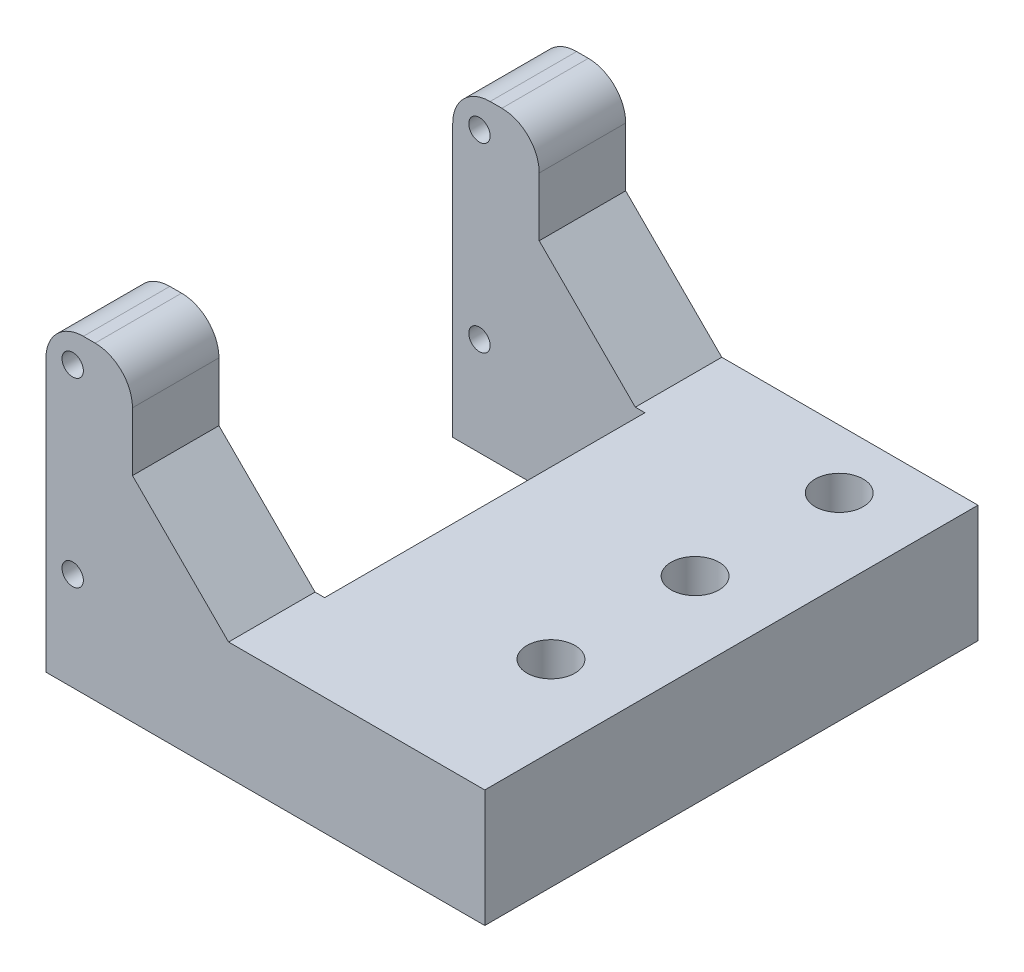
SolidWorks part; units mm, degrees
ref_plane "Plan de face" through (0, 0, 0) normal (0, 0, 1) x (1, 0, 0)
ref_plane "Plan de dessus" through (0, 0, 0) normal (0, 1, 0) x (1, 0, 0)
ref_plane "Plan de droite" through (0, 0, 0) normal (1, 0, 0) x (0, 0, -1)
sketch "Esquisse1" plane through (0, 0, 0) normal (0, 0, 1) x (1, 0, 0)
  line L1 (0, 0) -> (18, 0)
  line L2 (0, 0) -> (0, 29)
  line L3 (0, 29) -> (18, 29)
  line L4 (18, 0) -> (18, 29)
  dimension "D1" = 18
  dimension "D2" = 29
extrude "Boss.-Extru.1" add sketch "Esquisse1" along normal blind 46.2
sketch "Esquisse3" plane through (0, 0, 46.2) normal (0, 0, 1) x (1, 0, 0)
  line L0 (0, 29) -> (0, 0) construction
  line L3 (2.5, 9.2) -> (2.5, 26.2) construction
  line L4 (2.5, 26.2) -> (10.1767, 26.2) construction
  line L5 (0, 0) -> (18, 0) construction
  circle A2 centre (2.5, 26.2) radius 1
  circle A4 centre (2.5, 9.2) radius 1
  dimension "D1" = 2.5
  dimension "D5" = 17
  dimension "D3" = 2
  dimension "D2" = 9.2
extrude "Enlèv. mat.-Extru.1" cut sketch "Esquisse3" against normal through all
sketch "Esquisse4" plane through (0, 29, 0) normal (0, 1, 0) x (1, 0, 0)
  line L0 (0, -23.1) -> (18, -23.1) construction
  line L1 (0, -46.2) -> (0, 0) construction
  line L2 (18, -46.2) -> (18, 0) construction
  line L3 (0, -38.1) -> (0, -8.1)
  line L4 (0, -8.1) -> (18, -8.1)
  line L6 (18, -8.1) -> (18, -38.1)
  line L7 (18, 0) -> (0, 0) construction
  line L8 (0, -38.1) -> (18, -38.1)
  dimension "D1" = 8.1
extrude "Enlèv. mat.-Extru.2" cut sketch "Esquisse4" against normal through all
sketch "Esquisse5" plane through (0, 29, 0) normal (0, 1, 0) x (1, 0, 0)
  line L0 (18, 0) -> (0, 0) construction
  line L1 (18, -46.2) -> (26.1, -46.2)
  line L2 (18, -46.2) -> (18, 0)
  line L3 (18, 0) -> (26.1, 0)
  line L4 (26.1, -46.2) -> (26.1, 0)
  dimension "D1" = 8.1
extrude "Boss.-Extru.2" add sketch "Esquisse5" against normal up to vertex (29 mm away)
fillet "Congé1" radius 3.5 2 edges at (0, 29, 42.15) (0, 29, 4.05)
sketch "Esquisse7" plane through (0, 0, 0) normal (0, 0, -1) x (-1, 0, 0)
  line L1 (-26.1, 29) -> (-8.1, 29)
  line L2 (-26.1, 29) -> (-26.1, 11)
  line L3 (-26.1, 11) -> (-8.1, 11)
  line L4 (-8.1, 29) -> (-8.1, 11)
  dimension "D1" = 18
  dimension "D2" = 18
extrude "Enlèv. mat.-Extru.4" cut sketch "Esquisse7" against normal up to vertex
sketch "Esquisse8" plane through (0, 11, 0) normal (0, 1, 0) x (1, 0, 0)
  line L0 (26.1, 0) -> (8.1, 0) construction
  line L1 (26.1, -46.2) -> (41.1, -46.2)
  line L2 (26.1, -46.2) -> (26.1, 0)
  line L3 (26.1, 0) -> (41.1, 0)
  line L4 (41.1, -46.2) -> (41.1, 0)
  line L5 (33.6, -46.2) -> (33.6, 0) construction
  line L6 (33.6, -23.1) -> (26.1, -23.1) construction
  circle A0 centre (33.6, -5.5) radius 2.25
  circle A1 centre (33.6, -32.5) radius 2.25
  circle A2 centre (33.6, -19) radius 2.25
  dimension "D2" = 5.5
  dimension "D3" = 4.5
  dimension "D1" = 27
  dimension "D5" = 13.5
  dimension "D4" = 15
extrude "Boss.-Extru.3" add sketch "Esquisse8" against normal up to vertex (11 mm away)
chamfer "Chanfrein1" distance 9 angle 45 2 edges at (8.1, 11, 4.05) (8.1, 11, 42.15)
fillet "Congé2" radius 3.5 2 edges at (8.1, 29, 4.05) (8.1, 29, 42.15)
